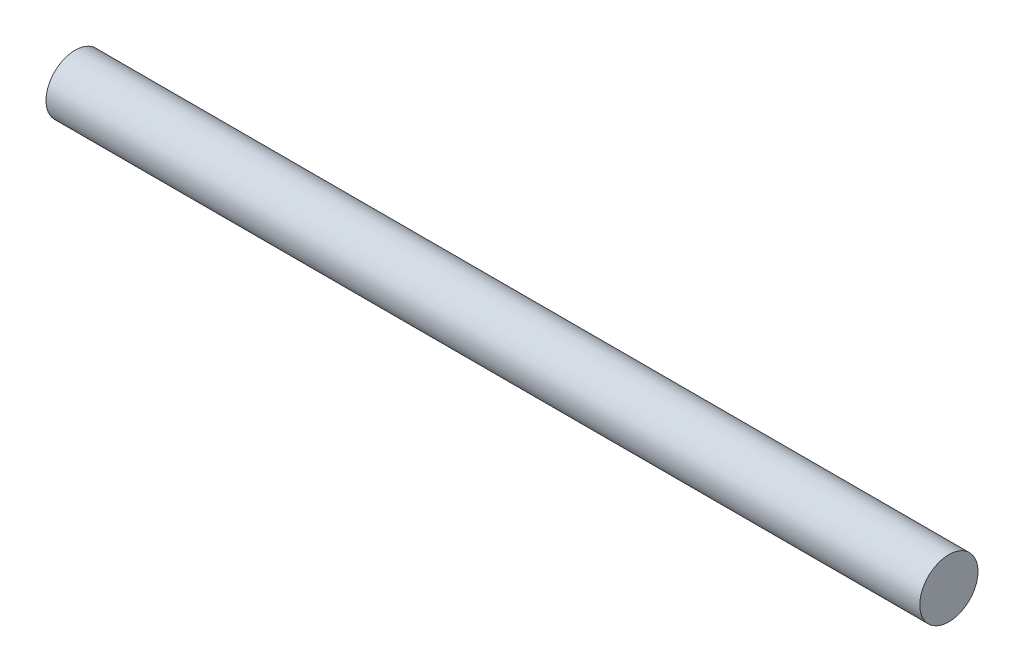
SolidWorks part; units mm, degrees
ref_plane "Plan de face" through (0, 0, 0) normal (0, 0, 1) x (1, 0, 0)
ref_plane "Plan de dessus" through (0, 0, 0) normal (0, 1, 0) x (1, 0, 0)
ref_plane "Plan de droite" through (0, 0, 0) normal (1, 0, 0) x (0, 0, -1)
sketch "Esquisse1" plane through (0, 0, 0) normal (0, 0, 1) x (1, 0, 0)
  line L1 (0, 0) -> (-120, 0)
  line L2 (0, 0) -> (0, 4)
  line L3 (0, 4) -> (-120, 4)
  line L4 (-120, 0) -> (-120, 4)
  dimension "D1" = 4
  dimension "D2" = 120
revolve "Révolution1" add sketch "Esquisse1" angle 360 about L3
